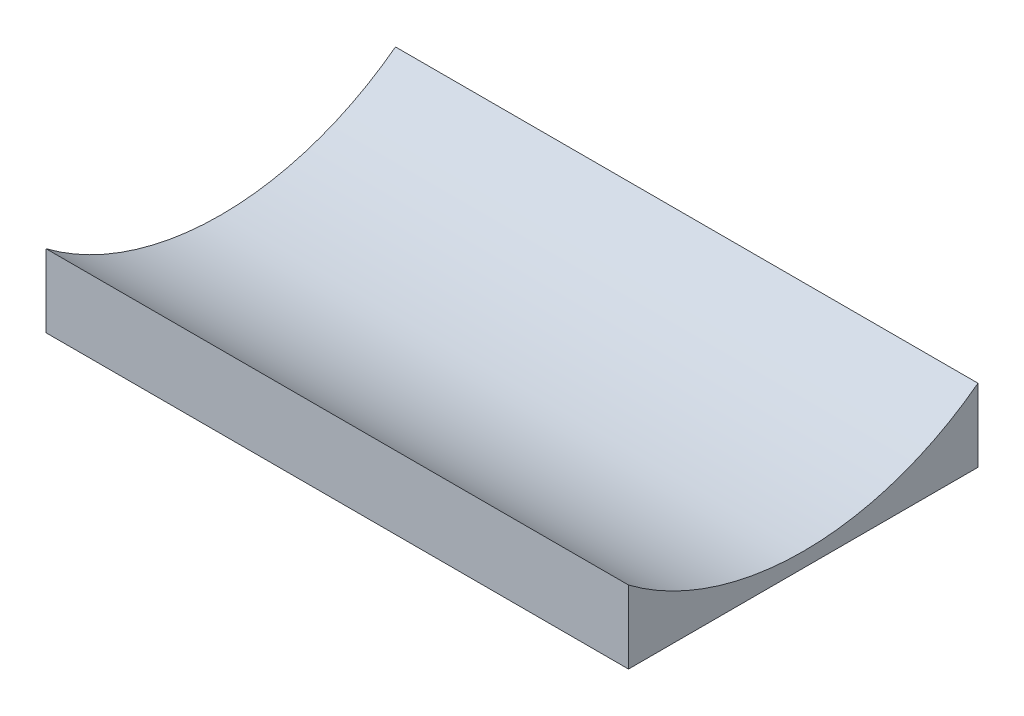
SolidWorks part; units mm, degrees
ref_plane "Front Plane" through (0, 0, 0) normal (0, 0, 1) x (1, 0, 0)
ref_plane "Top Plane" through (0, 0, 0) normal (0, 1, 0) x (1, 0, 0)
ref_plane "Right Plane" through (0, 0, 0) normal (1, 0, 0) x (0, 0, -1)
sketch "Sketch1" plane through (0, 0, 0) normal (0, 1, 0) x (1, 0, 0)
  line L1 (50, 30) -> (-50, 30)
  line L2 (50, 30) -> (50, -30)
  line L3 (50, -30) -> (-50, -30)
  line L4 (-50, 30) -> (-50, -30)
  line L5 (50, 30) -> (-50, -30) construction
  line L6 (50, -30) -> (-50, 30) construction
  point P0 (0, 0)
  dimension "D1" = 60
  dimension "D2" = 100
extrude "Boss-Extrude4" add sketch "Sketch1" along normal blind 10
sketch "Sketch2" plane through (50, 0, 0) normal (1, 0, 0) x (0, 0, -1)
  arc A0 (-30, 10) -> (30, 10) centre (0, 50) ccw
extrude "Cut-Extrude1" cut sketch "Sketch2" against normal blind 100 and the other way through all
sketch "Sketch3" plane through (50, 0, 0) normal (1, 0, 0) x (0, 0, -1)
  line L1 (-30, 0) -> (29.9979, 0)
  line L2 (-30, 0) -> (-30, -10)
  line L3 (-30, -10) -> (29.9979, -10)
  line L4 (29.9979, 0) -> (29.9979, -10)
  dimension "D1" = 59.9979
  dimension "D2" = 10
extrude "Boss-Extrude5" add sketch "Sketch3" against normal blind 100
sketch "Sketch4" plane through (0, 0, -29.9979) normal (0, 0, -1) x (-1, 0, 0)
  line L0 (50, -10) -> (50, 0) construction
  line L1 (-50, -10) -> (50, -10)
  line L2 (-50, -10) -> (-50, -5)
  line L3 (-50, -5) -> (50, -5)
  line L4 (50, -10) -> (50, -5)
  dimension "D1" = 5
extrude "Cut-Extrude2" cut sketch "Sketch4" against normal blind 60
sketch "Sketch5" plane through (0, 0, -29.9979) normal (0, 0, -1) x (-1, 0, 0)
  line L0 (-50, -5) -> (-50, 0) construction
  line L1 (-50, -2.5) -> (50, -2.5)
  line L2 (-50, -2.5) -> (-50, -5)
  line L3 (-50, -5) -> (50, -5)
  line L4 (50, -2.5) -> (50, -5)
  line L5 (50, -5) -> (-50, -5) construction
  dimension "D1" = 2.5
extrude "Cut-Extrude3" cut sketch "Sketch5" against normal blind 60
